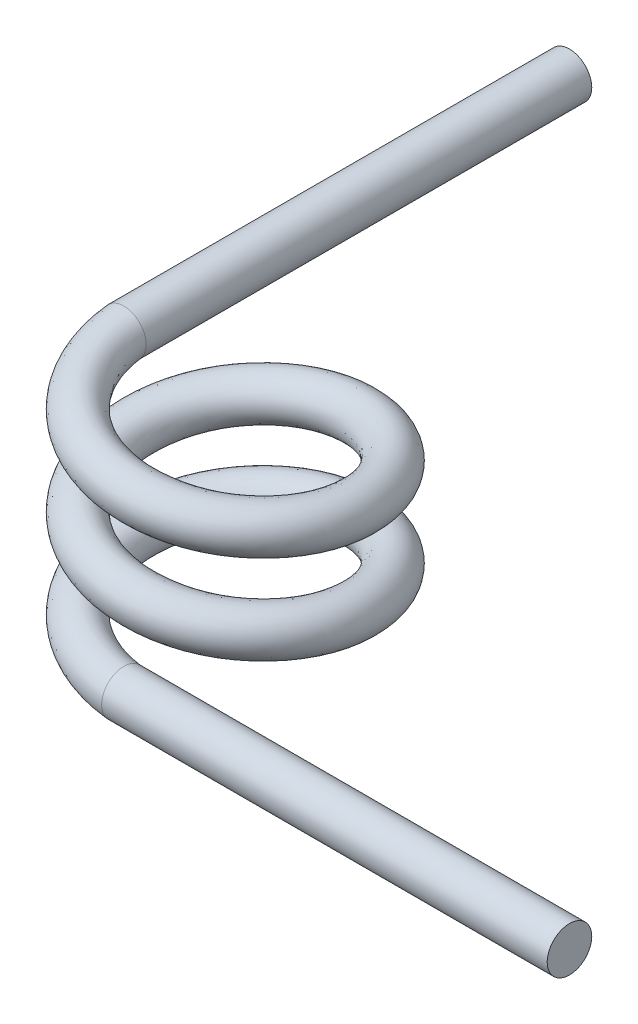
SolidWorks part; units mm, degrees
ref_plane "前视基准面" through (0, 0, 0) normal (0, 0, 1) x (1, 0, 0)
ref_plane "上视基准面" through (0, 0, 0) normal (0, 1, 0) x (1, 0, 0)
ref_plane "右视基准面" through (0, 0, 0) normal (1, 0, 0) x (0, 0, -1)
other "Configuration Table"
sketch "Sketch1" plane through (0, 0, 0) normal (0, 1, 0) x (1, 0, 0)
  circle A0 centre (0, 0) radius 1.25
  dimension "D1" = 2.5
curve "Helix/Spiral1" pitch 1 height 2.5 turns 2.5
ref_plane "Plane3" through (0, 0, 0) normal (0, 0, 1) x (1, 0, 0)
sketch "Sketch5" plane through (0, 0, 0) normal (0, 0, 1) x (1, 0, 0)
  circle A0 centre (-1.25, 2.5) radius 0.25
  spline S0 degree 3 poles (1.25, 0) (1.25, 0.0207) (1.1849, 0.0626) (0.9069, 0.125) (0.4908, 0.1875) (0, 0.25) (-0.4908, 0.3125) (-0.9069, 0.375) (-1.1849, 0.4375) (-1.2825, 0.5) (-1.1849, 0.5625) (-0.9069, 0.625) (-0.3521, 0.7083) (0.3521, 0.7917) (0.9069, 0.875) (1.1849, 0.9375) (1.2825, 1) (1.1849, 1.0625) (0.9069, 1.125) (0.3521, 1.2083) (-0.3521, 1.2917) (-0.9069, 1.375) (-1.1849, 1.4375) (-1.2825, 1.5) (-1.1849, 1.5625) (-0.9069, 1.625) (-0.3521, 1.7083) (0.3521, 1.7917) (0.9069, 1.875) (1.1849, 1.9375) (1.2825, 2) (1.1849, 2.0625) (0.9069, 2.125) (0.4908, 2.1875) (0, 2.25) (-0.4908, 2.3125) (-0.9069, 2.375) (-1.1849, 2.4374) (-1.25, 2.4793) (-1.25, 2.5) knots 0 0 0 0 0.025 0.05 0.075 0.1 0.125 0.15 0.175 0.2 0.225 0.25 0.275 0.325 0.35 0.375 0.4 0.425 0.45 0.475 0.525 0.55 0.575 0.6 0.625 0.65 0.675 0.725 0.75 0.775 0.8 0.825 0.85 0.875 0.9 0.925 0.95 0.975 1 1 1 1 construction
  dimension "D1" = 0.5
sweep "Sweep1" add profiles "Sketch5" path "Helix/Spiral1"
sketch "Sketch6" plane through (0, 0, 0) normal (0, 0, -1) x (-1, 0, 0)
  circle A0 centre (1.2499, 2.4982) radius 0.25
  spline S0 degree 3 poles (-1.25, 0) (-1.25, 0.0207) (-1.1849, 0.0626) (-0.9069, 0.125) (-0.4908, 0.1875) (0, 0.25) (0.4908, 0.3125) (0.9069, 0.375) (1.1849, 0.4375) (1.2825, 0.5) (1.1849, 0.5625) (0.9069, 0.625) (0.3521, 0.7083) (-0.3521, 0.7917) (-0.9069, 0.875) (-1.1849, 0.9375) (-1.2825, 1) (-1.1849, 1.0625) (-0.9069, 1.125) (-0.3521, 1.2083) (0.3521, 1.2917) (0.9069, 1.375) (1.1849, 1.4375) (1.2825, 1.5) (1.1849, 1.5625) (0.9069, 1.625) (0.3521, 1.7083) (-0.3521, 1.7917) (-0.9069, 1.875) (-1.1849, 1.9375) (-1.2825, 2) (-1.1849, 2.0625) (-0.9069, 2.125) (-0.4908, 2.1875) (0, 2.25) (0.4908, 2.3125) (0.9069, 2.375) (1.1849, 2.4374) (1.25, 2.4793) (1.25, 2.5) knots 0 0 0 0 0.025 0.05 0.075 0.1 0.125 0.15 0.175 0.2 0.225 0.25 0.275 0.325 0.35 0.375 0.4 0.425 0.45 0.475 0.525 0.55 0.575 0.6 0.625 0.65 0.675 0.725 0.75 0.775 0.8 0.825 0.85 0.875 0.9 0.925 0.95 0.975 1 1 1 1 construction
  dimension "D1" = 0.5
extrude "Boss-Extrude1" add sketch "Sketch6" along normal blind 5
sketch "Sketch9" plane through (0, 0, 0) normal (1, 0, 0) x (0, 0, -1)
  line L0 (0, 0) -> (0, 0.7612)
  line L1 (0, 0.7612) -> (-1.7134, 0.7612)
  line L2 (-1.7134, 0.7612) -> (-1.7134, -0.2611)
  line L3 (-1.7134, -0.2611) -> (0, -0.2611)
  line L4 (0, -0.2611) -> (0, 0)
sketch "Sketch10" plane through (0, 0, 0) normal (0, 0, 1) x (1, 0, 0)
  line L0 (0, 0) -> (0, 0.4767)
  line L1 (0, 0) -> (0, 0.7612) construction
  line L2 (0, 0.4767) -> (1.5965, 0.4767)
  line L3 (1.5965, 0.4767) -> (1.5965, -0.3389)
  line L4 (1.5965, -0.3389) -> (0, -0.3102)
  line L5 (0, -0.3102) -> (0, 0)
extrude "Cut-Extrude3" cut sketch "Sketch10" against normal through all both and the other way through all
sketch "Sketch11" plane through (0, 0, 0) normal (1, 0, 0) x (0, 0, -1)
  circle A0 centre (-1.25, 0.25) radius 0.25
  spline S0 degree 3 poles (0, 0) (-0.1626, 0.0207) (-0.4913, 0.0626) (-0.9068, 0.125) (-1.1849, 0.1875) (-1.2825, 0.25) (-1.1849, 0.3125) (-0.9069, 0.375) (-0.3521, 0.4583) (0.3521, 0.5417) (0.9069, 0.625) (1.1849, 0.6875) (1.2825, 0.75) (1.1849, 0.8125) (0.9069, 0.875) (0.3521, 0.9583) (-0.3521, 1.0417) (-0.9069, 1.125) (-1.1849, 1.1875) (-1.2825, 1.25) (-1.1849, 1.3125) (-0.9069, 1.375) (-0.3521, 1.4583) (0.3521, 1.5417) (0.9069, 1.625) (1.1849, 1.6875) (1.2825, 1.75) (1.1849, 1.8125) (0.9069, 1.875) (0.3521, 1.9583) (-0.3521, 2.0417) (-0.9069, 2.125) (-1.1849, 2.1875) (-1.2825, 2.25) (-1.1849, 2.3125) (-0.9068, 2.375) (-0.4913, 2.4374) (-0.1626, 2.4793) (0, 2.5) knots 0 0 0 0 0.025 0.05 0.075 0.1 0.125 0.15 0.175 0.225 0.25 0.275 0.3 0.325 0.35 0.375 0.425 0.45 0.475 0.5 0.525 0.55 0.575 0.625 0.65 0.675 0.7 0.725 0.75 0.775 0.825 0.85 0.875 0.9 0.925 0.95 0.975 1 1 1 1 construction
  dimension "D1" = 0.5
extrude "Boss-Extrude3" add sketch "Sketch11" along normal blind 5
sketch "Sketch12" plane through (0, 0, 0) normal (0, 1, 0) x (1, 0, 0)
  circle A0 centre (0, 0) radius 1.25 construction
  dimension "D1" = 2.5
sketch "Sketch13" plane through (0, 0, 0) normal (0, 1, 0) x (1, 0, 0)
  circle A0 centre (0, 0) radius 1.5008
